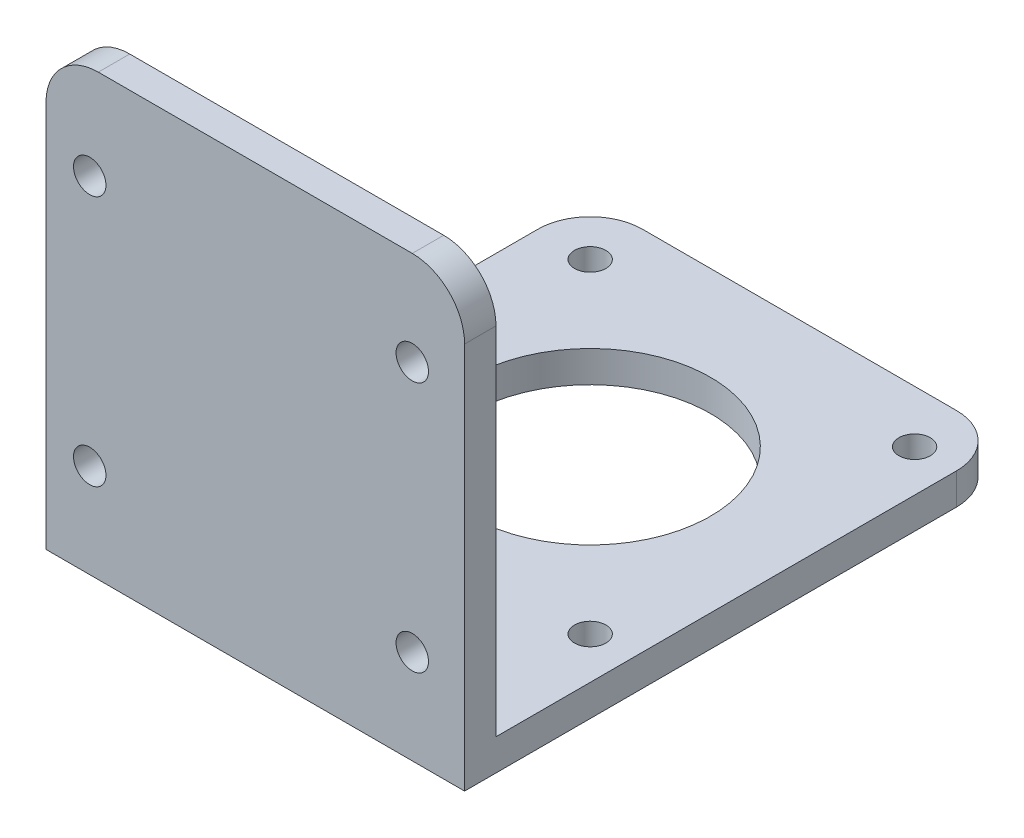
SolidWorks part; units mm, degrees
ref_plane "前视基准面" through (0, 0, 0) normal (0, 0, 1) x (1, 0, 0)
ref_plane "上视基准面" through (0, 0, 0) normal (0, 1, 0) x (1, 0, 0)
ref_plane "右视基准面" through (0, 0, 0) normal (1, 0, 0) x (0, 0, -1)
other "Configuration Table"
sketch "草图2" plane through (0, 0, 0) normal (0, 1, 0) x (1, 0, 0)
  line L1 (-26.7778, 24.7076) -> (3.2222, 24.7076)
  line L2 (-31.7778, 19.7076) -> (-31.7778, -27.2924)
  line L3 (-31.7778, -27.2924) -> (8.2222, -27.2924)
  line L4 (8.2222, 19.7076) -> (8.2222, -27.2924)
  arc A0 (-31.7778, 19.7076) -> (-26.7778, 24.7076) centre (-26.7778, 19.7076) cw
  arc A1 (3.2222, 24.7076) -> (8.2222, 19.7076) centre (3.2222, 19.7076) cw
  point P6 (-31.7778, 24.7076)
  point P9 (8.2222, 24.7076)
  dimension "D3" = 5
  dimension "D4" = 5
  dimension "D1" = 52
  dimension "D2" = 40
extrude "凸台-拉伸1" add sketch "草图2" along normal blind 3
sketch "草图3" plane through (0, 3, 0) normal (0, 1, 0) x (1, 0, 0)
  line L0 (8.2222, -27.2924) -> (8.2222, 19.7076) construction
  line L1 (-31.7778, -27.2924) -> (8.2222, -27.2924)
  line L2 (-31.7778, -27.2924) -> (-31.7778, -24.2924)
  line L3 (-31.7778, -24.2924) -> (8.2222, -24.2924)
  line L4 (8.2222, -27.2924) -> (8.2222, -24.2924)
  dimension "D1" = 3
extrude "凸台-拉伸2" add sketch "草图3" along normal blind 39
sketch "草图4" plane through (0, 0, 27.2924) normal (0, 0, 1) x (1, 0, 0)
  line L14 (-31.7778, 37) -> (-31.7778, 42)
  line L15 (-31.7778, 42) -> (-26.7778, 42)
  line L16 (3.2222, 42) -> (8.2222, 42)
  line L17 (8.2222, 42) -> (8.2222, 37)
  arc A2 (-26.7778, 42) -> (-31.7778, 37) centre (-26.7778, 37) ccw
  arc A3 (3.2222, 42) -> (8.2222, 37) centre (3.2222, 37) cw
  point P9 (-31.7778, 42)
  dimension "D1" = 5
  dimension "D2" = 5
extrude "切除-拉伸1" cut sketch "草图4" against normal up to next
sketch "草图5" plane through (0, 3, 0) normal (0, 1, 0) x (1, 0, 0)
  line L0 (-26.7778, 4.2076) -> (4.2222, 4.2076) construction
  line L1 (-26.7778, 19.7076) -> (4.2222, 19.7076) construction
  line L2 (-26.7778, 19.7076) -> (-26.7778, -11.2924) construction
  line L3 (-26.7778, -11.2924) -> (4.2222, -11.2924) construction
  line L4 (4.2222, 19.7076) -> (4.2222, -11.2924) construction
  line L5 (-11.2778, 19.7076) -> (-11.2778, -11.2924) construction
  circle A8 centre (-26.7778, 19.7076) radius 1.5
  circle A9 centre (4.2222, 19.7076) radius 1.5
  circle A10 centre (-26.7778, -11.2924) radius 1.5
  circle A11 centre (4.2222, -11.2924) radius 1.5
  circle A12 centre (-11.2778, 4.2076) radius 11.5
  dimension "D1" = 31
  dimension "D2" = 31
  dimension "D3" = 23
extrude "切除-拉伸2" cut sketch "草图5" against normal up to next contours A8 | A12 | A9 | A11 | A10
sketch "草图6" plane through (0, 0, 27.2924) normal (0, 0, 1) x (1, 0, 0)
  line L0 (-11.7778, 0) -> (-11.7778, 42) construction
  line L1 (-27.5976, 9) -> (3.2222, 9) construction
  line L2 (-27.5976, 9) -> (-27.5976, 33) construction
  line L3 (-27.5976, 33) -> (3.2222, 33) construction
  line L4 (3.2222, 9) -> (3.2222, 33) construction
  line L5 (-31.7778, 0) -> (8.2222, 0) construction
  line L6 (-26.7778, 42) -> (3.2222, 42) construction
  line L7 (8.2222, 37) -> (8.2222, 0) construction
  circle A0 centre (-27.5976, 9) radius 1.55
  circle A1 centre (-27.5976, 33) radius 1.55
  circle A2 centre (3.2222, 9) radius 1.55
  circle A3 centre (3.2222, 33) radius 1.55
  dimension "D1" = 5
  dimension "D2" = 24
  dimension "D3" = 9
extrude "切除-拉伸3" cut sketch "草图6" against normal up to next
